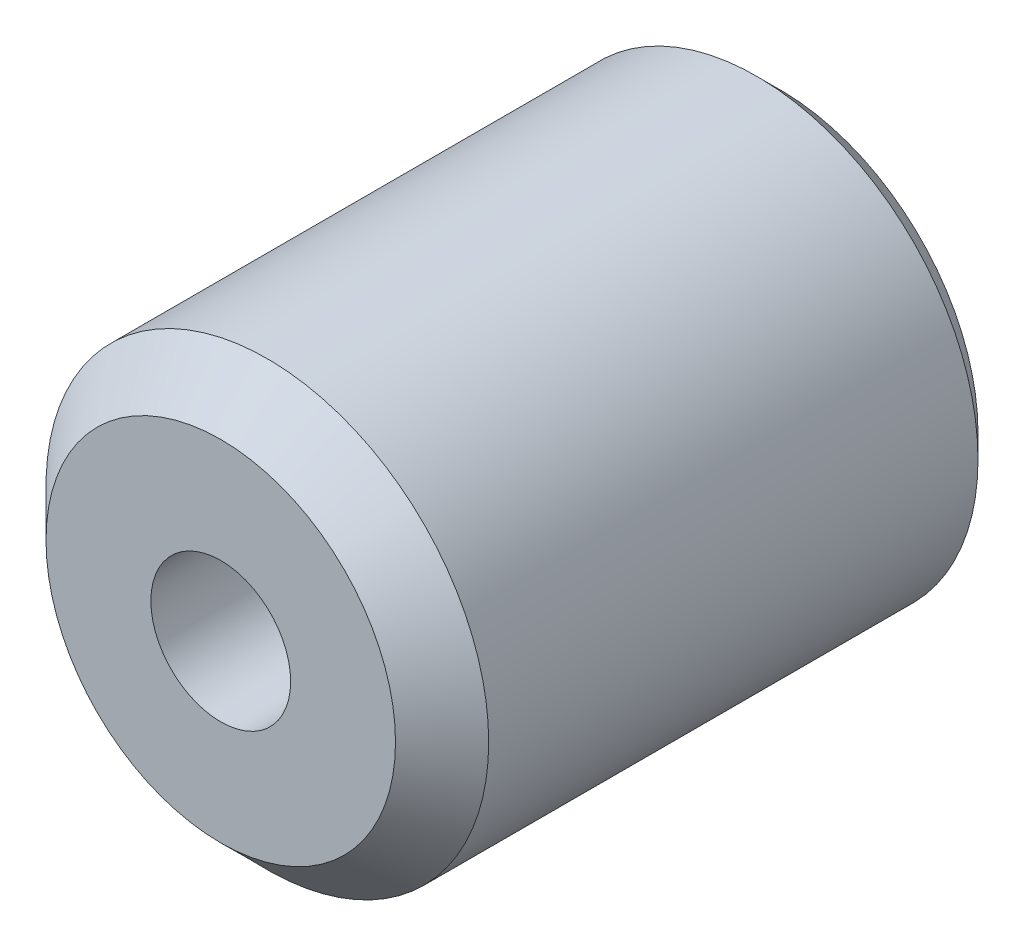
SolidWorks part; units mm, degrees
material "Copper"
ref_plane "Front Plane" through (0, 0, 0) normal (0, 0, 1) x (1, 0, 0)
ref_plane "Top Plane" through (0, 0, 0) normal (0, 1, 0) x (1, 0, 0)
ref_plane "Right Plane" through (0, 0, 0) normal (1, 0, 0) x (0, 0, -1)
sketch "Sketch1" plane through (0, 0, 0) normal (0, 0, 1) x (1, 0, 0)
  circle A0 centre (0, 0) radius 9.5
  dimension "D1" = 19
extrude "Boss-Extrude1" add sketch "Sketch1" along normal mid plane 24
chamfer "Chamfer1" distance 2 angle 45 1 edges at (9.5, 0, 12)
chamfer "Chamfer2" distance 1 angle 45 1 edges at (9.5, 0, -12)
sketch "Sketch2" plane through (0, 0, -12) normal (0, 0, -1) x (-1, 0, 0)
  circle A0 centre (0, 0) radius 7
extrude "Cut-Extrude1" cut sketch "Sketch2" against normal blind 14
sketch "Sketch3" plane through (0, 0, 2) normal (0, 0, -1) x (-1, 0, 0)
  circle A0 centre (0, 0) radius 3
extrude "Cut-Extrude2" cut sketch "Sketch3" against normal blind 14
